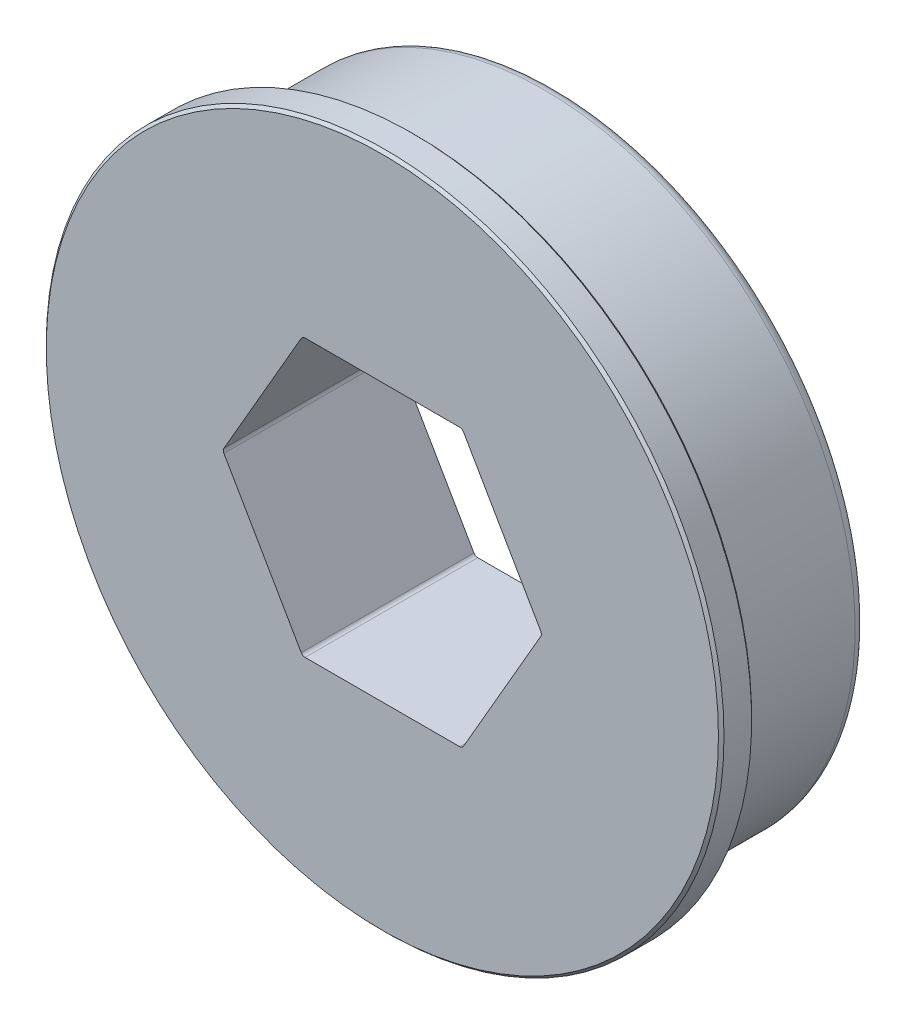
SolidWorks part; units mm, degrees
material "6061-T6 (SS)"
ref_plane "Front Plane" through (0, 0, 0) normal (0, 0, 1) x (1, 0, 0)
ref_plane "Top Plane" through (0, 0, 0) normal (0, 1, 0) x (1, 0, 0)
ref_plane "Right Plane" through (0, 0, 0) normal (1, 0, 0) x (0, 0, -1)
ref_plane "Plane1" through (0, 0, 0) normal (0, -1, 0) x (1, 0, 0)
sketch "Sketch1" plane through (0, 0, 0) normal (0, -1, 0) x (1, 0, 0)
  line L0 (15.5575, 7.9273) -> (0, 7.9273)
  line L1 (0, 7.9273) -> (0, 0)
  line L2 (0, 0) -> (14.2875, 0)
  line L3 (14.2875, 0) -> (14.2875, 5.8953)
  line L4 (14.2875, 5.8953) -> (13.97, 5.8953)
  line L5 (13.97, 5.8953) -> (13.97, 6.4033)
  line L6 (13.97, 6.4033) -> (15.5575, 6.4033)
  line L7 (15.5575, 6.4033) -> (15.5575, 7.9273)
  line L8 (0, 7.9273) -> (0, 0) construction
revolve "Revolve1" add sketch "Sketch1" angle 360 about L8
sketch "Sketch2" plane through (0, 0, 0) normal (0, 0, -1) x (-1, 0, 0)
  line L0 (3.6662, 6.35) -> (-3.6662, 6.35)
  line L1 (-3.6662, 6.35) -> (-7.3323, 0)
  line L2 (-7.3323, 0) -> (-3.6662, -6.35)
  line L3 (-3.6662, -6.35) -> (3.6662, -6.35)
  line L4 (3.6662, -6.35) -> (7.3323, 0)
  line L5 (7.3323, 0) -> (3.6662, 6.35)
  line L6 (3.6662, 6.35) -> (-3.6662, -6.35) construction
  line L8 (-3.8862, -6.7311) -> (-3.6662, -6.35) construction
  circle A0 centre (0, 0) radius 6.35 construction
  circle A1 centre (0, 0) radius 7.7724 construction
  dimension "D1" = 12.7
  dimension "D2" = 15.5448
  dimension "D3" = 0.4401
extrude "Cut-Extrude1" cut sketch "Sketch2" against normal through all
chamfer "Chamfer1" distance 0.127 angle 45 1 edges at (-15.5575, 0, 6.4033)
chamfer "Chamfer2" distance 0.127 angle 45 1 edges at (-15.5575, 0, 7.9273)
fillet "Fillet1" radius 0.508 1 edges at (-14.2875, 0, 0)
fillet "Fillet2" radius 0.2032 6 edges at (3.6662, 6.35, 3.9637) (7.3323, 0, 3.9637) (3.6662, -6.35, 3.9637) (-3.6662, -6.35, 3.9637) (-7.3323, 0, 3.9637) (-3.6662, 6.35, 3.9637)
move or copy body "Body-Move/Copy1" [suppressed] bodies to move or copy 104
